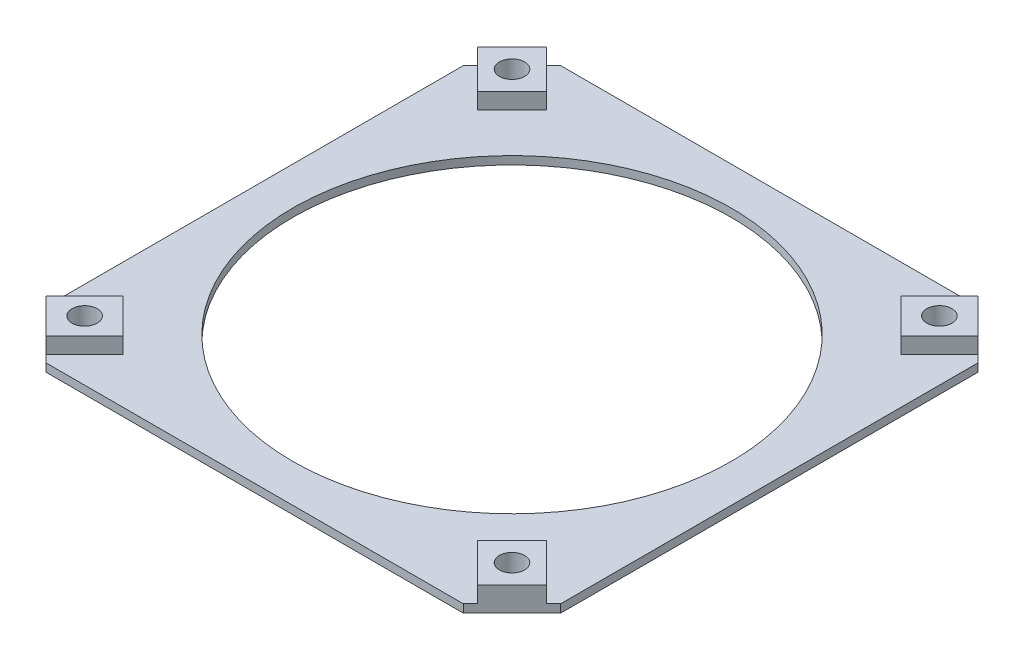
SolidWorks part; units mm, degrees
ref_plane "Front" through (0, 0, 0) normal (0, 0, 1) x (1, 0, 0)
ref_plane "Top" through (0, 0, 0) normal (0, 1, 0) x (1, 0, 0)
ref_plane "Right" through (0, 0, 0) normal (1, 0, 0) x (0, 0, -1)
sketch "Sketch1" plane through (0, 0, 0) normal (0, 1, 0) x (1, 0, 0)
  line L0 (31.68, 25.68) -> (25.68, 31.68)
  line L1 (25.68, -31.68) -> (-25.68, -31.68)
  line L2 (31.68, -25.68) -> (31.68, 25.68)
  line L3 (25.68, 31.68) -> (-25.68, 31.68)
  line L4 (-31.68, -25.68) -> (-31.68, 25.68)
  line L5 (31.68, -31.68) -> (-31.68, 31.68) construction
  line L6 (31.68, 31.68) -> (-31.68, -31.68) construction
  line L7 (-25.68, 31.68) -> (-31.68, 25.68)
  line L8 (-25.68, -31.68) -> (-31.68, -25.68)
  line L9 (31.68, -25.68) -> (25.68, -31.68)
  circle A0 centre (0, 0) radius 27
  point P0 (0, 0)
  dimension "D2" = 54
  dimension "D1" = 63.36
  dimension "D3" = 89.6046
extrude "Boss-Extrude1" add sketch "Sketch1" along normal blind 1
sketch "Sketch2" plane through (0, 1, 0) normal (0, 1, 0) x (1, 0, 0)
  line L0 (0, 0) -> (26.3044, 26.3044) construction
  line L1 (31.68, -25.68) -> (31.68, 25.68) construction
  line L2 (30.8013, 26.5587) -> (26.0501, 21.8074)
  line L3 (30.8013, 26.5587) -> (26.5587, 30.8013)
  line L4 (26.0501, 21.8074) -> (21.8074, 26.0501)
  line L5 (26.5587, 30.8013) -> (21.8074, 26.0501)
  line L6 (30.8013, 26.5587) -> (21.8074, 26.0501) construction
  line L7 (26.0501, 21.8074) -> (26.5587, 30.8013) construction
  line L9 (31.68, 25.68) -> (25.68, 31.68) construction
  line L10 (30.8013, -26.5587) -> (26.0501, -21.8074)
  line L11 (21.8074, -26.0501) -> (26.0501, -21.8074)
  line L12 (26.5587, -30.8013) -> (21.8074, -26.0501)
  line L13 (26.5587, -30.8013) -> (30.8013, -26.5587)
  line L14 (-26.5587, -30.8013) -> (-21.8074, -26.0501)
  line L15 (-26.0501, -21.8074) -> (-21.8074, -26.0501)
  line L16 (-30.8013, -26.5587) -> (-26.0501, -21.8074)
  line L17 (-30.8013, -26.5587) -> (-26.5587, -30.8013)
  line L18 (-30.8013, 26.5587) -> (-26.0501, 21.8074)
  line L19 (-21.8074, 26.0501) -> (-26.0501, 21.8074)
  line L20 (-26.5587, 30.8013) -> (-21.8074, 26.0501)
  line L21 (-26.5587, 30.8013) -> (-30.8013, 26.5587)
  line L22 (-25.68, 31.68) -> (-31.68, 25.68) construction
  line L23 (25.68, 31.68) -> (-25.68, 31.68) construction
  point P26 (0, 0)
  dimension "D1" = 37.2
  dimension "D2" = 45
  dimension "D3" = 6
  dimension "D4" = 4
  dimension "D5" = 0.8787
extrude "Boss-Extrude2" add sketch "Sketch2" along normal blind 2
hole_wizard "M3 Clearance Hole1" positions "Sketch3" profile "Sketch4" hole size "M3" standard "ISO" end condition through all
sketch "Sketch3" plane through (0, 3, 0) normal (0, 1, 0) x (1, 0, 0)
  point P0 (26.3044, 26.3044)
sketch "Sketch4" plane through (26.3044, 3, -26.3044) normal (1, 0, 0) x (0, 0, 1)
  line L0 (0, 0) -> (0, 3)
  line L1 (0, 3) -> (1.55, 3)
  line L2 (1.55, 3) -> (1.55, 0)
  line L5 (1.55, 0) -> (0, 0)
  line L11 (0, -6.35) -> (0, 107.95) construction
  dimension "Thru Hole Dia." = 3.1
  dimension "Thru Hole Depth" = 3
pattern_circular "CirPattern1" count 4 over 360 about axis through (0, 0, 0) along (0, 1, 0) of "M3 Clearance Hole1"
